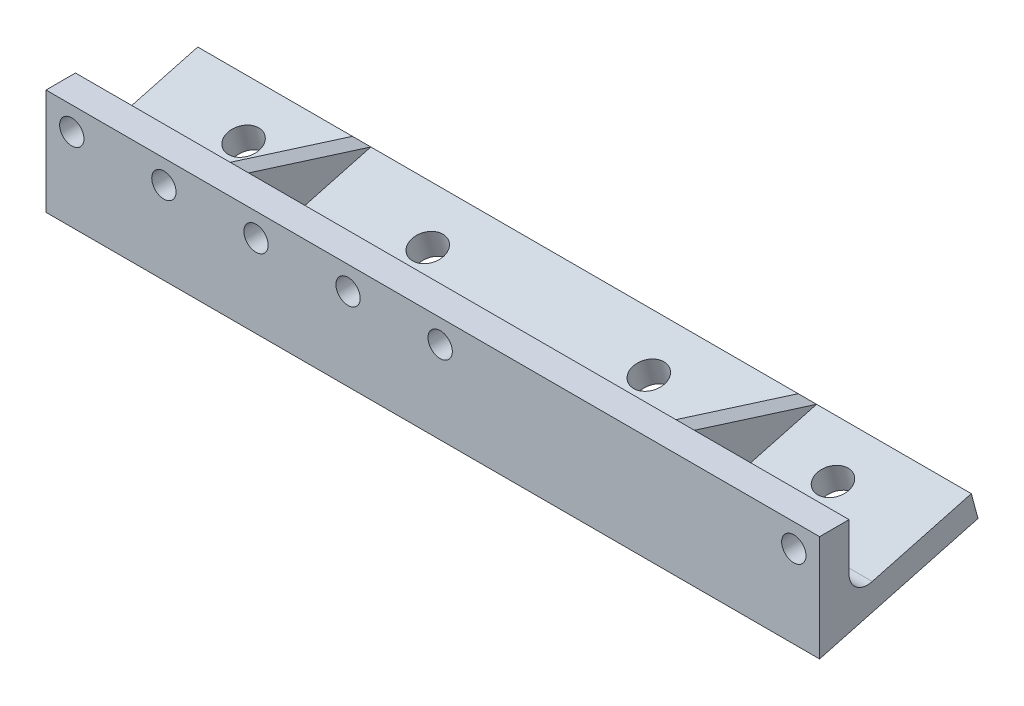
SolidWorks part; units mm, degrees
material "1060 合金"
ref_plane "前视基准面" through (0, 0, 0) normal (0, 0, 1) x (1, 0, 0)
ref_plane "上视基准面" through (0, 0, 0) normal (0, 1, 0) x (1, 0, 0)
ref_plane "右视基准面" through (0, 0, 0) normal (1, 0, 0) x (0, 0, -1)
sketch "草图1" plane through (0, 0, 0) normal (0, 1, 0) x (1, 0, 0)
  line L0 (0, 0) -> (170, 0) construction
  line L1 (170, 31.93) -> (170, -31.93)
  line L2 (15.8391, 73.3084) -> (162.1119, 41.7045)
  line L3 (15.8391, -73.3084) -> (162.1119, -41.7045)
  arc A0 (15.8391, 73.3084) -> (15.8391, -73.3084) centre (0, 0) ccw
  arc A1 (162.1119, -41.7045) -> (170, -31.93) centre (160, -31.93) ccw
  arc A2 (170, 31.93) -> (162.1119, 41.7045) centre (160, 31.93) ccw
  point P6 (170, 0)
  dimension "D1" = 150
  dimension "D4" = 20
  dimension "D5" = 20
  dimension "D2" = 170
  dimension "D3" = 63.86
extrude "凸台-拉伸1" add sketch "草图1" along normal blind 30
sketch "草图2" plane through (0, 30, 0) normal (0, 1, 0) x (1, 0, 0)
  circle A0 centre (0, 0) radius 44.45
  dimension "D1" = 88.9
extrude "切除-拉伸1" cut sketch "草图2" against normal blind 4
sketch "草图3" plane through (0, 26, 0) normal (0, 1, 0) x (1, 0, 0)
  line L0 (0, 0) -> (0, 90.3276) construction
  circle A0 centre (0, 0) radius 25.5
  circle A1 centre (0, 41) radius 2.25
  circle A2 centre (28.9914, 28.9914) radius 2.25
  circle A3 centre (41, 0) radius 2.25
  circle A4 centre (28.9914, -28.9914) radius 2.25
  circle A5 centre (0, -41) radius 2.25
  circle A6 centre (-28.9914, -28.9914) radius 2.25
  circle A7 centre (-41, 0) radius 2.25
  circle A8 centre (-28.9914, 28.9914) radius 2.25
  dimension "D1" = 51
  dimension "D3" = 4.5
  dimension "D2" = 41
  dimension "D4" = 8
extrude "切除-拉伸2" cut sketch "草图3" against normal through all contours A2 | A3 | A4 | A5 | A6 | A7 | A8 | A1 | A0
sketch "草图4" plane through (0, 30, 0) normal (0, 1, 0) x (1, 0, 0)
  line L0 (0, 0) -> (134, 0) construction
  line L1 (124, 18.5) -> (134, 18.5)
  line L2 (124, -18.5) -> (134, -18.5)
  arc A0 (134, -18.5) -> (134, 18.5) centre (134, 0) ccw
  arc A1 (124, 18.5) -> (124, -18.5) centre (124, 0) ccw
  dimension "D2" = 37
  dimension "D3" = 37
  dimension "D1" = 134
  dimension "D4" = 10
extrude "切除-拉伸3" cut sketch "草图4" against normal through all
sketch "草图5" plane through (0, 30, 0) normal (0, 1, 0) x (1, 0, 0)
  arc A0 (134, -18.5) -> (134, 18.5) centre (134, 0) ccw construction
  arc A1 (124, 18.5) -> (124, -18.5) centre (124, 0) ccw construction
  arc A2 (134, -18.5) -> (134, 18.5) centre (134, 0) ccw construction
  arc A3 (124, 18.5) -> (124, -18.5) centre (124, 0) ccw construction
  circle A4 centre (116.75, 25.5) radius 1.65
  circle A5 centre (141.25, 25.5) radius 1.65
  circle A6 centre (141.25, -25.5) radius 1.65
  circle A7 centre (116.75, -25.5) radius 1.65
  dimension "D1" = 3.3
  dimension "D2" = 3.3
  dimension "D3" = 3.3
  dimension "D4" = 3.3
  dimension "D7" = 25.5
  dimension "D5" = 7.25
  dimension "D6" = 25.5
  dimension "D8" = 7.25
  dimension "D9" = 7.25
extrude "切除-拉伸4" cut sketch "草图5" against normal through all
sketch "草图6" plane through (0, 30, 0) normal (0, 1, 0) x (1, 0, 0)
  line L0 (158, 42.5929) -> (158, -42.5929) construction
  line L2 (-52, 54.0463) -> (-52, -54.0463) construction
  line L6 (162.1119, 41.7045) -> (15.8391, 73.3084) construction
  line L7 (15.8391, -73.3084) -> (162.1119, -41.7045) construction
  line L8 (-52, 95) -> (-52, -95)
  line L9 (158, 95) -> (158, -95)
  line L10 (-52, 95) -> (158, 95)
  line L11 (-52, -95) -> (158, -95)
  line L15 (162.1119, 41.7045) -> (15.8391, 73.3084)
  line L16 (15.8391, -73.3084) -> (162.1119, -41.7045)
  line L17 (170, -31.93) -> (170, 31.93)
  line L18 (162.1119, 41.7045) -> (15.8391, 73.3084)
  line L19 (15.8391, -73.3084) -> (162.1119, -41.7045)
  line L20 (170, -31.93) -> (170, 31.93)
  arc A0 (15.8391, 73.3084) -> (15.8391, -73.3084) centre (0, 0) ccw construction
  arc A6 (170, 31.93) -> (162.1119, 41.7045) centre (160, 31.93) ccw
  arc A7 (15.8391, 73.3084) -> (15.8391, -73.3084) centre (0, 0) ccw
  arc A8 (162.1119, -41.7045) -> (170, -31.93) centre (160, -31.93) ccw
  arc A9 (170, 31.93) -> (162.1119, 41.7045) centre (160, 31.93) ccw
  arc A10 (15.8391, 73.3084) -> (15.8391, -73.3084) centre (0, 0) ccw
  arc A11 (162.1119, -41.7045) -> (170, -31.93) centre (160, -31.93) ccw
  point P8 (-52, 0)
  point P13 (158, 0)
  line M26 (162.1119, 41.7045) -> (15.8391, 73.3084)
  arc M27 (15.8391, 73.3084) -> (15.8391, -73.3084) centre (0, 0) ccw
  line M28 (15.8391, -73.3084) -> (162.1119, -41.7045)
  dimension "D3" = 190
  dimension "D1" = 210
  dimension "D2" = 52
  dimension "D4" = 190
  dimension "D5" = 0
extrude "凸台-拉伸2" add sketch "草图6" against normal blind 30 contours L10 L8 L9 M27 M26 | L8 L11 L9 M28 M27
sketch "草图7" plane through (0, 30, 0) normal (0, 1, 0) x (1, 0, 0)
  line L0 (-52, 54.0463) -> (-52, -54.0463)
  line L1 (158, 42.5929) -> (158, -42.5929)
  line L9 (162.1119, 41.7045) -> (158, 42.5929)
  line L10 (158, 42.5929) -> (158, 95)
  line L11 (158, 95) -> (-52, 95)
  line L12 (-52, 95) -> (-52, 54.0463)
  line L13 (-52, -54.0463) -> (-52, -95)
  line L14 (-52, -95) -> (158, -95)
  line L15 (158, -95) -> (158, -42.5929)
  line L16 (158, -42.5929) -> (162.1119, -41.7045)
  line L17 (170, -31.93) -> (170, 31.93)
  line L18 (162.1119, 41.7045) -> (158, 42.5929)
  line L21 (-52, 95) -> (-52, 54.0463)
  line L25 (158, -42.5929) -> (162.1119, -41.7045)
  line L26 (170, -31.93) -> (170, 31.93)
  arc A3 (170, 31.93) -> (162.1119, 41.7045) centre (160, 31.93) ccw
  arc A4 (-52, 54.0463) -> (-52, -54.0463) centre (0, 0) ccw
  arc A5 (162.1119, -41.7045) -> (170, -31.93) centre (160, -31.93) ccw
  arc A6 (170, 31.93) -> (162.1119, 41.7045) centre (160, 31.93) ccw
  arc A7 (-52, 54.0463) -> (-52, -54.0463) centre (0, 0) ccw
  arc A8 (162.1119, -41.7045) -> (170, -31.93) centre (160, -31.93) ccw
  arc M22 (170, 31.93) -> (162.1119, 41.7045) centre (160, 31.93) ccw
  line M23 (162.1119, 41.7045) -> (158, 42.5929)
  arc M27 (-52, 54.0463) -> (-52, -54.0463) centre (0, 0) ccw
  line M31 (158, -42.5929) -> (162.1119, -41.7045)
  arc M32 (162.1119, -41.7045) -> (170, -31.93) centre (160, -31.93) ccw
  line M33 (170, -31.93) -> (170, 31.93)
  dimension "D1" = 0
extrude "切除-拉伸5" cut sketch "草图7" against normal through all contours L0 M27 | L1 M23 M31 M32 M33 M22
sketch "草图9" plane through (-52, 0, 0) normal (-1, 0, 0) x (0, 0, 1)
  line L0 (-95, 20) -> (-60, 10.6218)
  line L1 (-95, 30) -> (95, 30) construction
  line L3 (-60, 10.6218) -> (-60, 30)
  line L5 (-95, 0) -> (-95, 30) construction
  line L7 (-95, 20) -> (-95, 30)
  line L8 (-95, 30) -> (-60, 30)
  dimension "D1" = 15
  dimension "D3" = 19.3782
  dimension "D4" = 35
  dimension "D5" = 10
extrude "切除-拉伸7" cut sketch "草图9" against normal through all contours L8 L3 L0 L7
sketch "草图8" plane through (-52, 0, 0) normal (-1, 0, 0) x (0, 0, 1)
  line L0 (0, 0) -> (52, 0)
  line L1 (-95, 0) -> (95, 0) construction
  line L2 (52, 0) -> (52, 17.3)
  line L3 (52, 17.3) -> (-52, 17.3)
  line L4 (-52, 17.3) -> (-52, 0)
  line L5 (-52, 0) -> (0, 0)
  line L6 (-60, 30) -> (95, 30) construction
  dimension "D1" = 52
  dimension "D2" = 52
  dimension "D3" = 12.7
sketch "草图10" plane through (-52, 0, 0) normal (-1, 0, 0) x (0, 0, 1)
  line L0 (-95, 12.7531) -> (-47.4049, 0) construction
  line L1 (-95, 0) -> (-95, 20) construction
  line L2 (-95, 0) -> (95, 0) construction
  line L3 (-95, 20) -> (-60, 10.6218) construction
  line L6 (-95, 12.7531) -> (-52, 1.2313)
  line L7 (-52, 1.2313) -> (-52, 0)
  line L8 (-95, 12.7531) -> (-95, 0)
  line L9 (-95, 0) -> (-52, 0)
  line L10 (-52, 17.3) -> (-52, 0) construction
  dimension "D1" = 7
extrude "切除-拉伸8" cut sketch "草图10" against normal through all
extrude "切除-拉伸9" cut sketch "草图8" against normal through all
fillet "圆角1" radius 5 1 edges at (53, 10.6218, -60)
sketch "草图11" plane through (-52, 0, 0) normal (-1, 0, 0) x (0, 0, 1)
  line L0 (-95, 12.7531) -> (-93.1883, 19.5145)
  line L1 (-95, 20) -> (-66.2941, 12.3083) construction
  line L2 (-93.1883, 19.5145) -> (-95, 20)
  line L3 (-95, 20) -> (-95, 12.7531)
extrude "切除-拉伸10" cut sketch "草图11" against normal through all
sketch "草图12" plane through (-52, 0, 0) normal (-1, 0, 0) x (0, 0, 1)
  line L0 (-93.1883, 19.5145) -> (-60, 30)
  line L10 (-93.1883, 19.5145) -> (-95, 12.7531)
  line L11 (-95, 12.7531) -> (-52, 1.2313)
  line L12 (-52, 1.2313) -> (-52, 17.3)
  line L13 (-52, 17.3) -> (52, 17.3)
  line L14 (52, 17.3) -> (52, 0)
  line L15 (52, 0) -> (95, 0)
  line L16 (95, 0) -> (95, 30)
  line L17 (95, 30) -> (-60, 30)
  line L18 (-60, 30) -> (-60, 17.1379)
  line L19 (-66.2941, 12.3083) -> (-93.1883, 19.5145)
  line L28 (-60, 30) -> (-60, 17.1379)
  line L29 (-66.2941, 12.3083) -> (-93.1883, 19.5145)
  arc A1 (-66.2941, 12.3083) -> (-60, 17.1379) centre (-65, 17.1379) ccw
  arc A2 (-66.2941, 12.3083) -> (-60, 17.1379) centre (-65, 17.1379) ccw
  dimension "D1" = 0
extrude "凸台-拉伸3" add sketch "草图12" against normal blind 5
sketch "草图13" plane through (158, 0, 0) normal (1, 0, 0) x (0, 0, -1)
  line L3 (66.2941, 12.3083) -> (93.1883, 19.5145)
  line L4 (93.1883, 19.5145) -> (60, 30)
  line L5 (60, 30) -> (60, 17.1379)
  line L6 (66.2941, 12.3083) -> (93.1883, 19.5145)
  line L7 (93.1883, 19.5145) -> (60, 30)
  line L8 (60, 30) -> (60, 17.1379)
  arc A1 (60, 17.1379) -> (66.2941, 12.3083) centre (65, 17.1379) ccw
  arc A2 (60, 17.1379) -> (66.2941, 12.3083) centre (65, 17.1379) ccw
  dimension "D1" = 0
extrude "凸台-拉伸4" add sketch "草图13" against normal blind 5
sketch "草图14" plane through (0, -5.0897, -1.3638) normal (0, 0.9659, 0.2588) x (1, 0, 0)
  line L0 (153, 67.2208) -> (153, 95.0637) construction
  line L3 (153, 95.0637) -> (-47, 95.0637) construction
  circle A0 centre (-27, 82.0637) radius 4.25
  circle A1 centre (23, 82.0637) radius 4.25
  circle A2 centre (83, 82.0637) radius 4.25
  circle A3 centre (133, 82.0637) radius 4.25
  dimension "D1" = 8.5
  dimension "D2" = 160
  dimension "D3" = 20
  dimension "D4" = 50
  dimension "D5" = 50
  dimension "D6" = 13
extrude "切除-拉伸11" cut sketch "草图14" against normal through all
sketch "草图16" plane through (-52, 0, 0) normal (-1, 0, 0) x (0, 0, 1)
  line L0 (-60, 30) -> (95, 30) construction
  line L1 (95, 0) -> (52, 0)
  line L2 (95, 0) -> (95, 30)
  line L3 (95, 30) -> (52, 30)
  line L4 (52, 0) -> (52, 30)
extrude "切除-拉伸12" cut sketch "草图16" against normal through all
ref_plane "基准面1" through (0, -11.8512, -3.1755) normal (0, -0.9659, -0.2588) x (-1, 0, 0)
sketch "草图18" plane through (0, 30, 0) normal (0, 1, 0) x (1, 0, 0)
  line L1 (-52, -52) -> (158, -52)
  line L2 (-52, -52) -> (-52, -57)
  line L3 (-52, -57) -> (158, -57)
  line L4 (158, -52) -> (158, -57)
  dimension "D1" = 5
extrude "凸台-拉伸7" add sketch "草图18" against normal up to surface (56.6355 mm away) up to plane "基准面1"
sketch "草图19" plane through (-52, 0, 0) normal (-1, 0, 0) x (0, 0, 1)
  line L0 (57, -27.9752) -> (90.1883, -36.868)
  line L1 (90.1883, -36.868) -> (92, -30.1065)
  line L2 (92, -30.1065) -> (57, -20.7283)
  line L3 (57, -27.9752) -> (57, 30) construction
  line L4 (57, -20.7283) -> (57, -27.9752)
  line L5 (52, -26.6355) -> (57, -27.9752) construction
  dimension "D1" = 7
  dimension "D2" = 40
extrude "凸台-拉伸8" add sketch "草图19" against normal up to surface (210 mm away) up to face at (158, 8.1654, -14.9098)
sketch "草图20" plane through (-52, 0, 0) normal (-1, 0, 0) x (0, 0, 1)
  line L0 (92, -30.1065) -> (57, -20.7283) construction
  line L1 (57, -20.7283) -> (57, 30) construction
  line L2 (92, -30.1065) -> (57, -20.7283)
  line L3 (57, -20.7283) -> (57, 30)
  line L4 (57, 30) -> (92, -30.1065)
extrude "凸台-拉伸9" add sketch "草图20" against normal blind 5
sketch "草图21" plane through (158, 0, 0) normal (1, 0, 0) x (0, 0, -1)
  line L3 (-57, 30) -> (-92, -30.1065)
  line L4 (-92, -30.1065) -> (-57, -20.7283)
  line L5 (-57, -20.7283) -> (-57, 30)
  line L6 (-57, 30) -> (-92, -30.1065)
  line L7 (-92, -30.1065) -> (-57, -20.7283)
  line L8 (-57, -20.7283) -> (-57, 30)
  dimension "D1" = 0
extrude "凸台-拉伸10" add sketch "草图21" against normal blind 5
sketch "草图22" plane through (0, -5.0897, -1.3638) normal (0, 0.9659, 0.2588) x (1, 0, 0)
  line L0 (-47, -96.6573) -> (-47, -47.2932) construction
  line L2 (153, -96.6573) -> (153, -60.4226) construction
  circle A0 centre (-27, -77.9363) radius 4.25
  circle A1 centre (23, -69.9363) radius 4.25
  circle A2 centre (83, -69.9363) radius 4.25
  circle A3 centre (133, -77.9363) radius 4.25
  circle A4 centre (133, 82.0637) radius 4.25 construction
  circle A5 centre (-27, 82.0637) radius 4.25 construction
  circle A6 centre (23, 82.0637) radius 4.25 construction
  circle A7 centre (83, 82.0637) radius 4.25 construction
  dimension "D1" = 8.5
  dimension "D7" = 152
  dimension "D6" = 152
  dimension "D8" = 50
  dimension "D4" = 160
  dimension "D5" = 160
  dimension "D2" = 20
  dimension "D3" = 20
  dimension "D9" = 50
extrude "切除-拉伸13" cut sketch "草图22" against normal through all
fillet "圆角2" radius 5 1 edges at (53, -20.7283, 57)
sketch "草图23" plane through (-52, 0, 0) normal (-1, 0, 0) x (0, 0, 1)
  line L0 (-52, 17.3) -> (-52, 40.5241)
  line L1 (-52, 17.3) -> (-52, -43.9123)
  line L2 (-52, -43.9123) -> (98.6729, -43.9123)
  line L3 (98.6729, -43.9123) -> (98.6729, 40.5241)
  line L4 (98.6729, 40.5241) -> (-52, 40.5241)
extrude "切除-拉伸14" cut sketch "草图23" against normal through all
sketch "草图24" plane through (0, 0, -60) normal (0, 0, -1) x (-1, 0, 0)
  line L0 (-153, 30) -> (47, 30) construction
  circle A0 centre (-151, 23.65) radius 3.3
  circle A1 centre (45, 23.65) radius 3.3
  circle A2 centre (20, 23.65) radius 3.3
  circle A3 centre (-5, 23.65) radius 3.3
  circle A4 centre (-30, 23.65) radius 3.3
  circle A5 centre (-55, 23.65) radius 3.3
  point P12 (-43.0629, 25.0702)
  point P17 (0, 0)
  dimension "D1" = 6.6
  dimension "D2" = 7
  dimension "D3" = 7
  dimension "D4" = 25
  dimension "D5" = 25
  dimension "D6" = 25
  dimension "D7" = 25
  dimension "D8" = 6.35
ref_plane "基准面3" through (-7.5, 0, 0) normal (-1, 0, 0) x (0, 0, 1)
sketch "草图25" plane through (-7.5, 0, 0) normal (-1, 0, 0) x (0, 0, 1)
  line L3 (-93.1883, 19.5145) -> (-66.2941, 12.3083)
  line L4 (-60, 30) -> (-93.1883, 19.5145)
  line L5 (-60, 17.1379) -> (-60, 30)
  line L6 (-93.1883, 19.5145) -> (-66.2941, 12.3083)
  line L7 (-60, 30) -> (-93.1883, 19.5145)
  line L8 (-60, 17.1379) -> (-60, 30)
  arc A1 (-66.2941, 12.3083) -> (-60, 17.1379) centre (-65, 17.1379) ccw
  arc A2 (-66.2941, 12.3083) -> (-60, 17.1379) centre (-65, 17.1379) ccw
  dimension "D1" = 0
extrude "凸台-拉伸11" add sketch "草图25" along normal mid plane 5
ref_plane "基准面4" through (113.5, 0, 0) normal (1, 0, 0) x (0, 0, -1)
sketch "草图26" plane through (113.5, 0, 0) normal (1, 0, 0) x (0, 0, -1)
  line L3 (60, 30) -> (60, 17.1379)
  line L4 (93.1883, 19.5145) -> (60, 30)
  line L5 (66.2941, 12.3083) -> (93.1883, 19.5145)
  line L6 (60, 30) -> (60, 17.1379)
  line L7 (93.1883, 19.5145) -> (60, 30)
  line L8 (66.2941, 12.3083) -> (93.1883, 19.5145)
  arc A1 (60, 17.1379) -> (66.2941, 12.3083) centre (65, 17.1379) ccw
  arc A2 (60, 17.1379) -> (66.2941, 12.3083) centre (65, 17.1379) ccw
  dimension "D1" = 0
extrude "凸台-拉伸12" add sketch "草图26" along normal mid plane 5
sketch "草图27" plane through (153, 0, 0) normal (-1, 0, 0) x (0, 0, 1)
  line L3 (-60, 17.1379) -> (-60, 30)
  line L4 (-60, 30) -> (-93.1883, 19.5145)
  line L5 (-93.1883, 19.5145) -> (-66.2941, 12.3083)
  line L6 (-60, 17.1379) -> (-60, 30)
  line L7 (-60, 30) -> (-93.1883, 19.5145)
  line L8 (-93.1883, 19.5145) -> (-66.2941, 12.3083)
  arc A1 (-66.2941, 12.3083) -> (-60, 17.1379) centre (-65, 17.1379) ccw
  arc A2 (-66.2941, 12.3083) -> (-60, 17.1379) centre (-65, 17.1379) ccw
  dimension "D1" = 0
extrude "切除-拉伸15" cut sketch "草图27" against normal blind 5
extrude "切除-拉伸16" cut sketch "草图24" against normal through all
sketch "草图28" plane through (-47, 0, 0) normal (1, 0, 0) x (0, 0, -1)
  line L5 (66.2941, 12.3083) -> (93.1883, 19.5145)
  line L6 (93.1883, 19.5145) -> (60, 30)
  line L7 (60, 30) -> (60, 26.2749)
  line L8 (60, 26.2749) -> (60, 21.0251)
  line L9 (60, 21.0251) -> (60, 17.1379)
  line L10 (66.2941, 12.3083) -> (93.1883, 19.5145)
  line L11 (93.1883, 19.5145) -> (60, 30)
  line L12 (60, 30) -> (60, 26.2749)
  line L13 (60, 26.2749) -> (60, 21.0251)
  line L14 (60, 21.0251) -> (60, 17.1379)
  arc A1 (60, 17.1379) -> (66.2941, 12.3083) centre (65, 17.1379) ccw
  arc A2 (60, 17.1379) -> (66.2941, 12.3083) centre (65, 17.1379) ccw
  dimension "D1" = 0
extrude "切除-拉伸17" cut sketch "草图28" against normal blind 5
